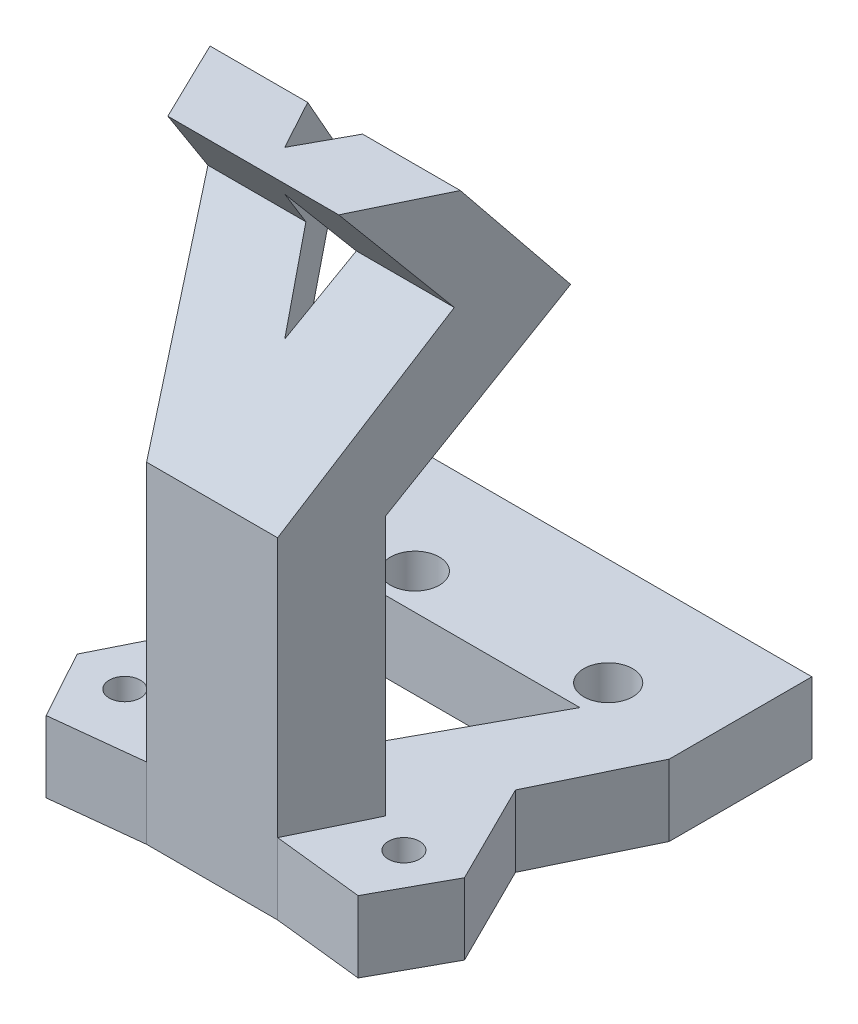
SolidWorks part; units mm, degrees
ref_plane "Front Plane" through (0, 0, 0) normal (0, 0, 1) x (1, 0, 0)
ref_plane "Top Plane" through (0, 0, 0) normal (0, 1, 0) x (1, 0, 0)
ref_plane "Right Plane" through (0, 0, 0) normal (1, 0, 0) x (0, 0, -1)
sketch "Sketch2" plane through (0, 0, 0) normal (0, 1, 0) x (1, 0, 0)
  line L0 (-47.1248, 0) -> (47.1248, 0) construction
  line L1 (-131.7903, 0) -> (131.7903, 0) construction
  line L2 (47.1248, 0) -> (-58.69, 0) construction
  line L3 (0, 0) -> (0, 70.6117) construction
  line L4 (0, 70.6117) -> (0, -77.9144) construction
  line L5 (-27.1, 0) -> (27.1, 0) construction
  line L6 (27.1, 0) -> (27.1, 20) construction
  line L7 (-27.1, 0) -> (27.1, 0)
  line L8 (27.1, 0) -> (27.1, 20)
  line L9 (27.1, 20) -> (-27.1, 20)
  line L10 (0, -131.4832) -> (0, 131.4832) construction
  line L11 (-27.1, 0) -> (-27.1, 20) construction
  line L12 (-47.1248, 0) -> (58.69, 0) construction
  line L13 (-27.1, 0) -> (-27.1, 20)
  point P4 (0, 0)
  point P8 (0, 0)
  point P19 (0, 20)
  dimension "D1" = 20
  dimension "D2" = 27.1
extrude "Boss-Extrude1" add sketch "Sketch2" along normal blind 10
ref_plane "Plane1" through (0, 5, 0) normal (0, 1, 0) x (1, 0, 0)
sketch "Sketch4" plane through (0, 10, 0) normal (0, 1, 0) x (1, 0, 0)
  line L0 (-27.1, 10) -> (-27.1, 0) construction
  line L1 (-55, 0) -> (55, 0) construction
  line L2 (-27.1, 20) -> (-27.1, 0) construction
  line L3 (-27.1, 0) -> (-27.1, 10) construction
  line L4 (-27.1, 10) -> (27.1, 10) construction
  line L5 (27.1, 0) -> (27.1, 20) construction
  line L6 (27.1, 10) -> (27.1, 0) construction
  line L8 (27.1, 0) -> (27.1, 5) construction
  line L9 (27.1, 5) -> (-27.1, 5) construction
  line L10 (0, 0) -> (27.1, 0) construction
  line L11 (-27.1, 0) -> (27.1, 0) construction
  line L12 (27.1, 0) -> (13.55, 0) construction
  line L13 (-13.55, 10) -> (-13.55, 0) construction
  line L14 (13.55, 0) -> (13.55, 10) construction
  line L15 (0, -27.3312) -> (0, 27.3312) construction
  circle A0 centre (13.55, 5) radius 2.1825
  circle A1 centre (-13.55, 5) radius 2.1825
  dimension "D1" = 4.365
extrude "Cut-Extrude1" cut sketch "Sketch4" against normal blind 10
sketch "Sketch5" plane through (0, 5, 0) normal (0, 1, 0) x (1, 0, 0)
  line L2 (-5.5, 0) -> (5.5, 0) construction
  line L4 (-27.1, 0) -> (-9.1823, -36.9742)
  line L6 (0, -27.3312) -> (0, 27.3312) construction
  line L7 (-9.1823, -36.9742) -> (9.1823, -36.9742)
  line L9 (27.1, 0) -> (9.1823, -36.9742)
  line L12 (-27.1, 0) -> (-14.58, 0)
  line L16 (-14.58, 0) -> (0, -26.7931)
  line L17 (14.58, 0) -> (0, -26.7931)
  line L18 (27.1, 0) -> (14.58, 0)
  line L19 (-27.1, 20) -> (-27.1, 0) construction
  point P17 (0, -36.9742)
  point P18 (0, 0)
  dimension "D3" = 18.3647
extrude "Boss-Extrude2" add sketch "Sketch5" along normal blind 5
sketch "Sketch9" plane through (0, 10, 0) normal (0, 1, 0) x (1, 0, 0)
  line L0 (0, 20) -> (0, -6.1) construction
  line L1 (27.1, 20) -> (-27.1, 20) construction
  line L2 (0, -27.3312) -> (0, 27.3312) construction
  line L3 (0, -6.1) -> (0, -26.7931) construction
  line L4 (0, -26.7931) -> (33.0841, -26.7931) construction
  line L5 (33.0841, -26.7931) -> (-31.5504, -26.7931) construction
  dimension "D1" = 26.1
sketch "Sketch10" plane through (0, 0, 0) normal (1, 0, 0) x (0, 0, -1)
  line L0 (-26.7931, 10) -> (-36.9742, 10) construction
  line L1 (-36.9742, 10) -> (-36.9742, 82.8) construction
  line L2 (-26.7931, 10) -> (-26.7931, 70.9936) construction
  line L3 (-26.7931, 10) -> (-26.7931, 46.4)
  line L4 (-26.7931, 46.4) -> (-9.3053, 70.0334)
  line L5 (-9.3053, 70.0334) -> (-19.7255, 84.1155)
  line L6 (-19.7255, 84.1155) -> (-31.2001, 84.1155)
  line L7 (-31.2001, 84.1155) -> (-20.2921, 70.0594)
  line L8 (-20.2921, 70.0594) -> (-36.9742, 46.4)
  line L9 (-36.9742, 46.4) -> (-36.9742, 10)
  line L10 (-36.9742, 10) -> (-26.7931, 10)
  point P12 (-36.9742, 46.4)
  point P13 (-36.9742, 46.4)
  dimension "D1" = 36.4
  dimension "D2" = 216.5
  dimension "D3" = 29.4
  dimension "D4" = 107
  dimension "D5" = 107
extrude "Boss-Extrude4" add sketch "Sketch10" along normal mid plane 56
sketch "Sketch12" plane through (0, 0, 0) normal (0, 1, 0) x (1, 0, 0)
  line L1 (-14.58, 0) -> (14.58, 0)
  line L4 (-27.1, 0) -> (-9.1823, -36.9742)
  line L7 (-9.1823, -36.9742) -> (9.1823, -36.9742)
  line L9 (27.1, 0) -> (9.1823, -36.9742)
  line L16 (-14.58, 0) -> (0, -26.7931)
  line L17 (14.58, 0) -> (0, -26.7931)
  line L20 (-27.1, 0) -> (-49.7625, -38.9547)
  line L21 (-49.7625, -38.9547) -> (46.0387, -38.9547)
  line L22 (46.0387, -38.9547) -> (27.1, 0)
  point P17 (0, -36.9742)
  point P18 (0, 0)
  dimension "D3" = 18.3647
extrude "Cut-Extrude2" cut sketch "Sketch12" along normal blind 106
sketch "Sketch14" plane through (0, 0, 0) normal (0, 1, 0) x (1, 0, 0)
  line L4 (-27.1, 0) -> (-9.1823, -36.9742)
  line L7 (-9.1823, -36.9742) -> (9.1823, -36.9742)
  line L9 (27.1, 0) -> (9.1823, -36.9742)
  line L12 (-27.1, 0) -> (-14.58, 0)
  line L16 (-14.58, 0) -> (0, -26.7931)
  line L17 (14.58, 0) -> (0, -26.7931)
  line L18 (27.1, 0) -> (14.58, 0)
  point P17 (0, -36.9742)
  point P18 (0, 0)
  dimension "D3" = 18.3647
extrude "Boss-Extrude5" add sketch "Sketch14" along normal blind 5
sketch "Sketch15" plane through (0, 0, 0) normal (0, 1, 0) x (1, 0, 0)
  line L0 (20.0659, -14.5154) -> (27.1464, -28.7435)
  line L1 (27.1464, -28.7435) -> (21.8653, -38.3747)
  line L2 (21.8653, -38.3747) -> (9.1823, -36.9742)
  line L3 (9.1823, -36.9742) -> (20.0659, -14.5154)
  line L4 (0, -27.3312) -> (0, 27.3312) construction
  line L5 (-21.8653, -38.3747) -> (-9.1823, -36.9742)
  line L6 (-27.1464, -28.7435) -> (-21.8653, -38.3747)
  line L7 (-20.0659, -14.5154) -> (-27.1464, -28.7435)
  line L8 (-9.1823, -36.9742) -> (-20.0659, -14.5154)
  line L9 (22.5907, -9.3053) -> (17.541, -19.7255) construction
extrude "Boss-Extrude6" add sketch "Sketch15" along normal blind 10
sketch "Sketch16" plane through (0, 10, 0) normal (0, 1, 0) x (1, 0, 0)
  line L0 (9.1823, -36.9742) -> (20.0659, -14.5154) construction
  line L1 (20.0659, -14.5154) -> (14.6241, -25.7448) construction
  line L2 (14.6241, -25.7448) -> (24.5059, -33.5591) construction
  line L3 (21.8653, -38.3747) -> (27.1464, -28.7435) construction
  line L4 (24.5059, -33.5591) -> (19.565, -29.6519) construction
  line L5 (0, -27.3312) -> (0, 27.3312) construction
  circle A0 centre (19.565, -29.6519) radius 2.1825
  circle A1 centre (-19.565, -29.6519) radius 2.1825
  dimension "D1" = 4.365
extrude "Cut-Extrude4" cut sketch "Sketch16" against normal blind 10
sketch "Sketch17" plane through (0, 10, 0) normal (0, 1, 0) x (1, 0, 0)
  line L0 (13.55, 5) -> (0, 5) construction
  line L1 (0, 20) -> (0, -6.1) construction
  line L2 (-13.55, 5) -> (0, 5) construction
  line L3 (0, -27.3312) -> (0, 27.3312) construction
  circle A0 centre (-13.55, 5) radius 3.4296
  circle A1 centre (13.55, 5) radius 3.4296
extrude "Cut-Extrude5" cut sketch "Sketch17" against normal blind 8.6
